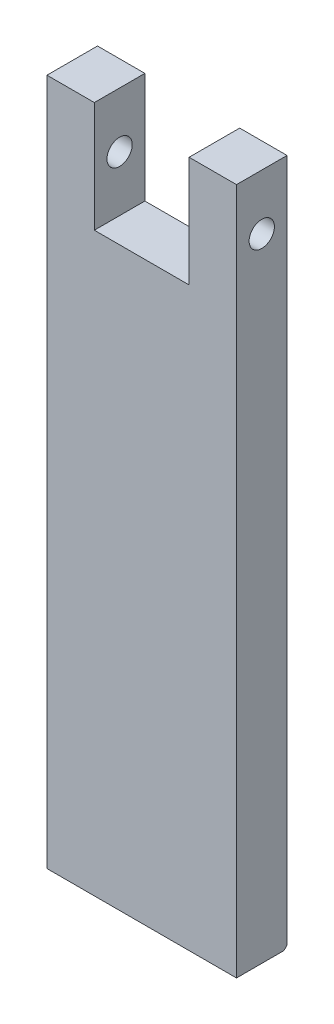
SolidWorks part; units mm, degrees
ref_plane "Front Plane" through (0, 0, 0) normal (0, 0, 1) x (1, 0, 0)
ref_plane "Top Plane" through (0, 0, 0) normal (0, 1, 0) x (1, 0, 0)
ref_plane "Right Plane" through (0, 0, 0) normal (1, 0, 0) x (0, 0, -1)
sketch "Sketch1" plane through (0, 0, 0) normal (0, 0, 1) x (1, 0, 0)
  line L1 (0, 0) -> (60, 0)
  line L2 (0, 0) -> (0, 250)
  line L3 (0, 250) -> (60, 250)
  line L4 (60, 0) -> (60, 250)
extrude "Boss-Extrude1" add sketch "Sketch1" along normal blind 16
chamfer "Chamfer1" distance 1 angle 45 1 edges at (30, 0, 0)
sketch "Sketch2" plane through (0, 0, 0) normal (0, -1, 0) x (-1, 0, 0)
  line L0 (-60, -8.5) -> (0, -8.5) construction
  line L1 (-60, -16) -> (-60, -1) construction
  line L2 (0, -16) -> (0, -1) construction
  line L3 (-30, 0) -> (-30, -16) construction
  line L4 (0, 0) -> (-60, 0) construction
  line L5 (0, -16) -> (-60, -16) construction
  line L6 (-41.5, -1) -> (-41.5, -16)
  line L7 (-18.5, -1) -> (-18.5, -16)
  line L8 (-18.5, 0) -> (-18.5, -16) construction
  line L9 (0, -1) -> (-60, -1) construction
  line L10 (-41.5, 0) -> (-41.5, -16) construction
  circle A0 centre (-41.5, -8.5) radius 2
  circle A1 centre (-18.5, -8.5) radius 2
  dimension "D1" = 11.5
  dimension "D2" = 11.5
extrude "Cut-Extrude1" cut sketch "Sketch2" against normal blind 15 contours A0 | A1
sketch "Sketch5" plane through (0, 0, 0) normal (0, 0, -1) x (-1, 0, 0)
  line L0 (-30, 0) -> (-30, 200) construction
  line L1 (0, 0) -> (-60, 0) construction
  line L3 (-15, 182.5) -> (-45, 182.5)
  line L4 (-15, 182.5) -> (-15, 217.5)
  line L5 (-15, 217.5) -> (-45, 217.5)
  line L6 (-45, 182.5) -> (-45, 217.5)
  line L7 (-15, 182.5) -> (-45, 217.5) construction
  line L8 (-15, 217.5) -> (-45, 182.5) construction
  dimension "D1" = 200
extrude "Cut-Extrude4" cut sketch "Sketch5" against normal up to next
sketch "Sketch6" plane through (45, 0, 0) normal (-1, 0, 0) x (0, 0, 1)
  line L0 (8, 182.5) -> (8, 217.5) construction
  line L1 (16, 182.5) -> (0, 182.5) construction
  line L2 (16, 217.5) -> (0, 217.5) construction
  circle A0 centre (8, 200) radius 4
extrude "Cut-Extrude5" cut sketch "Sketch6" against normal through all both and the other way through all
sketch "Sketch7" plane through (0, 0, 0) normal (0, 0, -1) x (-1, 0, 0)
  line L0 (-60, 1) -> (-60, 250) construction
  line L1 (0, 250) -> (-60, 250)
  line L2 (0, 250) -> (0, 217.5)
  line L3 (0, 217.5) -> (-60, 217.5)
  line L4 (-60, 250) -> (-60, 217.5)
extrude "Cut-Extrude6" cut sketch "Sketch7" against normal through all
